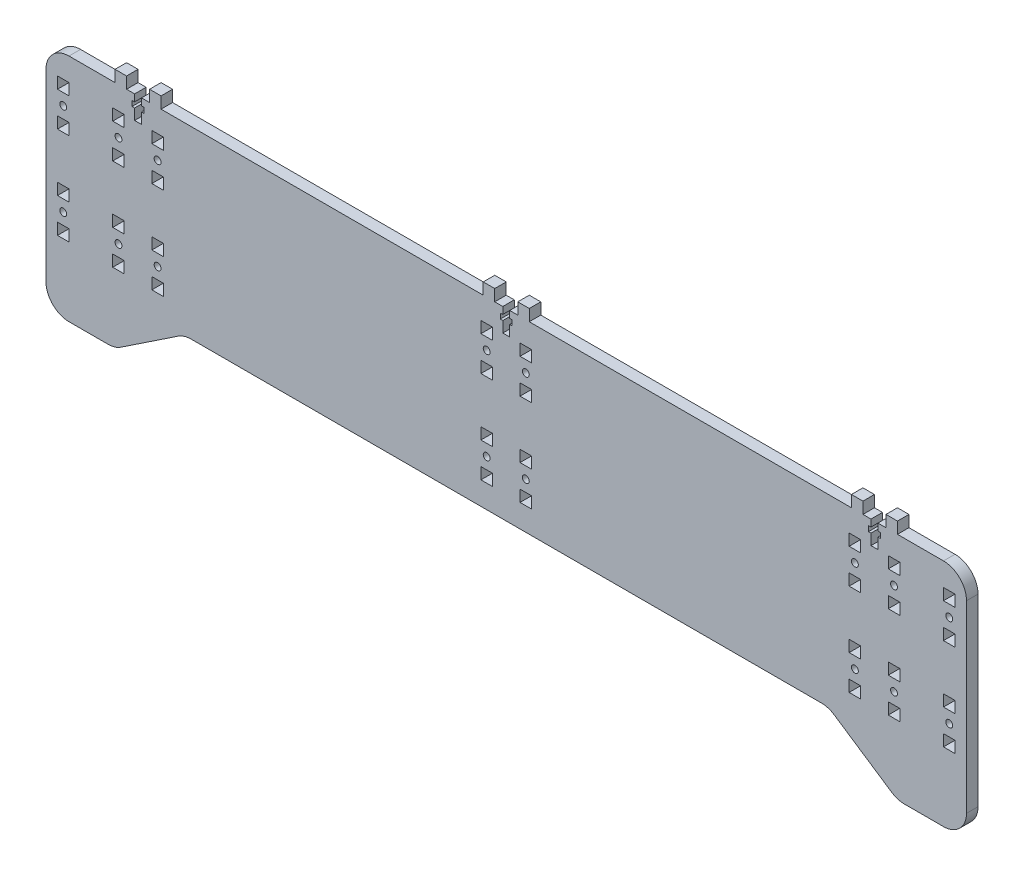
SolidWorks part; units mm, degrees
ref_plane "Front Plane" through (0, 0, 0) normal (0, 0, 1) x (1, 0, 0)
ref_plane "Top Plane" through (0, 0, 0) normal (0, 1, 0) x (1, 0, 0)
ref_plane "Right Plane" through (0, 0, 0) normal (1, 0, 0) x (0, 0, -1)
sketch "Sketch1" plane through (0, 0, 0) normal (0, 0, 1) x (1, 0, 0)
  line L0 (0, 0) -> (194.9917, 0) construction
  line L1 (0, 0) -> (0, -11.2208) construction
  line L2 (1.5, 0) -> (5, 0)
  line L3 (5, 5) -> (10, 5)
  line L4 (10, 5) -> (10, 0)
  line L5 (5, 5) -> (5, 0)
  line L6 (-1.5, 0) -> (-5, 0)
  line L7 (-5, 0) -> (-5, 5)
  line L8 (-5, 5) -> (-10, 5)
  line L9 (-10, 5) -> (-10, 0)
  line L10 (1.5, 0) -> (-1.5, 0) construction
  line L11 (-1.5, 0) -> (-1.5, -3)
  line L12 (-1.5, -5.3) -> (-2.6, -5.3)
  line L13 (2.6, -3) -> (2.6, -5.3)
  line L14 (-2.6, -3) -> (-1.5, -3)
  line L15 (-1.5, -5.3) -> (-1.5, -10)
  line L16 (-1.5, -10) -> (1.5, -10)
  line L17 (1.5, -10) -> (1.5, -5.3)
  line L18 (1.5, -3) -> (2.6, -3)
  line L19 (-2.6, -5.3) -> (-2.6, -3)
  line L20 (2.6, -5.3) -> (1.5, -5.3)
  line L21 (1.5, -3) -> (1.5, 0)
  line L22 (0, -10) -> (0, 0) construction
  line L23 (170, 5) -> (170, 0)
  line L24 (165, 5) -> (170, 5)
  line L25 (165, 5) -> (165, 0)
  line L26 (161.5, 0) -> (165, 0)
  line L27 (161.5, -3) -> (161.5, 0)
  line L28 (161.5, -3) -> (162.6, -3)
  line L29 (162.6, -3) -> (162.6, -5.3)
  line L30 (162.6, -5.3) -> (161.5, -5.3)
  line L31 (161.5, -10) -> (161.5, -5.3)
  line L32 (158.5, -10) -> (161.5, -10)
  line L33 (158.5, -5.3) -> (158.5, -10)
  line L34 (158.5, -5.3) -> (157.4, -5.3)
  line L35 (157.4, -5.3) -> (157.4, -3)
  line L36 (157.4, -3) -> (158.5, -3)
  line L37 (158.5, 0) -> (158.5, -3)
  line L38 (158.5, 0) -> (155, 0)
  line L39 (155, 0) -> (155, 5)
  line L40 (155, 5) -> (150, 5)
  line L41 (150, 5) -> (150, 0)
  line L42 (0, 0) -> (0, -60) construction
  line L43 (-150, 5) -> (-150, 0)
  line L44 (-155, 5) -> (-150, 5)
  line L45 (-155, 0) -> (-155, 5)
  line L46 (-158.5, 0) -> (-155, 0)
  line L47 (-158.5, 0) -> (-158.5, -3)
  line L48 (-157.4, -3) -> (-158.5, -3)
  line L49 (-157.4, -5.3) -> (-157.4, -3)
  line L50 (-158.5, -5.3) -> (-157.4, -5.3)
  line L51 (-158.5, -5.3) -> (-158.5, -10)
  line L52 (-158.5, -10) -> (-161.5, -10)
  line L53 (-161.5, -10) -> (-161.5, -5.3)
  line L54 (-162.6, -5.3) -> (-161.5, -5.3)
  line L55 (-162.6, -3) -> (-162.6, -5.3)
  line L56 (-161.5, -3) -> (-162.6, -3)
  line L57 (-161.5, -3) -> (-161.5, 0)
  line L58 (-161.5, 0) -> (-165, 0)
  line L59 (-165, 5) -> (-165, 0)
  line L60 (-165, 5) -> (-170, 5)
  line L61 (-170, 5) -> (-170, 0)
  line L63 (-10, 0) -> (-150, 0)
  line L64 (-170, 0) -> (-200, 0)
  line L65 (-200, 0) -> (-200, -100)
  line L66 (-200, -100) -> (200, -100) construction
  line L67 (200, -100) -> (200, 0)
  line L68 (200, 0) -> (170, 0)
  line L69 (10, 0) -> (150, 0)
  line L70 (-200, -60) -> (200, -60) construction
  line L71 (-160, -10) -> (-160, -60) construction
  line L72 (160, -10) -> (160, -60) construction
  line L73 (-151.5, -20) -> (-151.5, -60) construction
  line L74 (-200, -100) -> (-170, -100)
  line L75 (-170, -100) -> (-140, -80)
  line L76 (-140, -80) -> (140, -80)
  line L77 (140, -80) -> (170, -100)
  line L78 (170, -100) -> (200, -100)
  point P31 (0, -34.8981)
  point P84 (0, 0)
  point P85 (0, 0)
  line B0 (151.5, -55) -> (151.5, -65) construction
  line B1 (154, -55) -> (154, -50)
  line B2 (154, -55) -> (149, -55)
  line B3 (149, -55) -> (149, -50)
  line B4 (154, -50) -> (149, -50)
  line B5 (154, -65) -> (154, -70)
  line B6 (154, -65) -> (149, -65)
  line B7 (149, -65) -> (149, -70)
  line B8 (154, -70) -> (149, -70)
  line B9 (151.5, -60) -> (158.4724, -60) construction
  circle B10 centre (151.5, -60) radius 1.5
  line B11 (8.5, -55) -> (8.5, -65) construction
  line B12 (11, -55) -> (11, -50)
  line B13 (11, -55) -> (6, -55)
  line B14 (6, -55) -> (6, -50)
  line B15 (11, -50) -> (6, -50)
  line B16 (11, -65) -> (11, -70)
  line B17 (11, -65) -> (6, -65)
  line B18 (6, -65) -> (6, -70)
  line B19 (11, -70) -> (6, -70)
  line B20 (8.5, -60) -> (15.4724, -60) construction
  circle B21 centre (8.5, -60) radius 1.5
  line B22 (-151.5, -55) -> (-151.5, -65) construction
  line B23 (-149, -55) -> (-149, -50)
  line B24 (-149, -55) -> (-154, -55)
  line B25 (-154, -55) -> (-154, -50)
  line B26 (-149, -50) -> (-154, -50)
  line B27 (-149, -65) -> (-149, -70)
  line B28 (-149, -65) -> (-154, -65)
  line B29 (-154, -65) -> (-154, -70)
  line B30 (-149, -70) -> (-154, -70)
  line B31 (-151.5, -60) -> (-144.5276, -60) construction
  circle B32 centre (-151.5, -60) radius 1.5
  line B33 (-151.5, -15) -> (-151.5, -25) construction
  line B34 (-149, -15) -> (-149, -10)
  line B35 (-149, -15) -> (-154, -15)
  line B36 (-154, -15) -> (-154, -10)
  line B37 (-149, -10) -> (-154, -10)
  line B38 (-149, -25) -> (-149, -30)
  line B39 (-149, -25) -> (-154, -25)
  line B40 (-154, -25) -> (-154, -30)
  line B41 (-149, -30) -> (-154, -30)
  line B42 (-151.5, -20) -> (-144.5276, -20) construction
  circle B43 centre (-151.5, -20) radius 1.5
  line B44 (8.5, -15) -> (8.5, -25) construction
  line B45 (11, -15) -> (11, -10)
  line B46 (11, -15) -> (6, -15)
  line B47 (6, -15) -> (6, -10)
  line B48 (11, -10) -> (6, -10)
  line B49 (11, -25) -> (11, -30)
  line B50 (11, -25) -> (6, -25)
  line B51 (6, -25) -> (6, -30)
  line B52 (11, -30) -> (6, -30)
  line B53 (8.5, -20) -> (15.4724, -20) construction
  circle B54 centre (8.5, -20) radius 1.5
  line B55 (151.5, -15) -> (151.5, -25) construction
  line B56 (154, -15) -> (154, -10)
  line B57 (154, -15) -> (149, -15)
  line B58 (149, -15) -> (149, -10)
  line B59 (154, -10) -> (149, -10)
  line B60 (154, -25) -> (154, -30)
  line B61 (154, -25) -> (149, -25)
  line B62 (149, -25) -> (149, -30)
  line B63 (154, -30) -> (149, -30)
  line B64 (151.5, -20) -> (158.4724, -20) construction
  circle B65 centre (151.5, -20) radius 1.5
  line B66 (192.5, -15) -> (192.5, -25) construction
  line B67 (195, -15) -> (195, -10)
  line B68 (195, -15) -> (190, -15)
  line B69 (190, -15) -> (190, -10)
  line B70 (195, -10) -> (190, -10)
  line B71 (195, -25) -> (195, -30)
  line B72 (195, -25) -> (190, -25)
  line B73 (190, -25) -> (190, -30)
  line B74 (195, -30) -> (190, -30)
  line B75 (192.5, -20) -> (199.4724, -20) construction
  circle B76 centre (192.5, -20) radius 1.5
  line B77 (192.5, -55) -> (192.5, -65) construction
  line B78 (195, -55) -> (195, -50)
  line B79 (195, -55) -> (190, -55)
  line B80 (190, -55) -> (190, -50)
  line B81 (195, -50) -> (190, -50)
  line B82 (195, -65) -> (195, -70)
  line B83 (195, -65) -> (190, -65)
  line B84 (190, -65) -> (190, -70)
  line B85 (195, -70) -> (190, -70)
  line B86 (192.5, -60) -> (199.4724, -60) construction
  circle B87 centre (192.5, -60) radius 1.5
  line B88 (-192.5, -55) -> (-192.5, -65) construction
  line B89 (-190, -55) -> (-190, -50)
  line B90 (-190, -55) -> (-195, -55)
  line B91 (-195, -55) -> (-195, -50)
  line B92 (-190, -50) -> (-195, -50)
  line B93 (-190, -65) -> (-190, -70)
  line B94 (-190, -65) -> (-195, -65)
  line B95 (-195, -65) -> (-195, -70)
  line B96 (-190, -70) -> (-195, -70)
  line B97 (-192.5, -60) -> (-185.5276, -60) construction
  circle B98 centre (-192.5, -60) radius 1.5
  line B99 (-192.5, -15) -> (-192.5, -25) construction
  line B100 (-190, -15) -> (-190, -10)
  line B101 (-190, -15) -> (-195, -15)
  line B102 (-195, -15) -> (-195, -10)
  line B103 (-190, -10) -> (-195, -10)
  line B104 (-190, -25) -> (-190, -30)
  line B105 (-190, -25) -> (-195, -25)
  line B106 (-195, -25) -> (-195, -30)
  line B107 (-190, -30) -> (-195, -30)
  line B108 (-192.5, -20) -> (-185.5276, -20) construction
  circle B109 centre (-192.5, -20) radius 1.5
  line B110 (171, -15) -> (171, -10)
  line B111 (171, -15) -> (166, -15)
  line B112 (166, -15) -> (166, -10)
  line B113 (171, -10) -> (166, -10)
  line B114 (171, -25) -> (171, -30)
  line B115 (171, -25) -> (166, -25)
  line B116 (166, -25) -> (166, -30)
  line B117 (171, -30) -> (166, -30)
  line B118 (168.5, -20) -> (175.4724, -20) construction
  circle B119 centre (168.5, -20) radius 1.5
  line B120 (171, -55) -> (171, -50)
  line B121 (171, -55) -> (166, -55)
  line B122 (166, -55) -> (166, -50)
  line B123 (171, -50) -> (166, -50)
  line B124 (171, -65) -> (171, -70)
  line B125 (171, -65) -> (166, -65)
  line B126 (166, -65) -> (166, -70)
  line B127 (171, -70) -> (166, -70)
  line B128 (168.5, -60) -> (175.4724, -60) construction
  circle B129 centre (168.5, -60) radius 1.5
  line B130 (-11, -55) -> (-11, -50)
  line B131 (-11, -55) -> (-6, -55)
  line B132 (-6, -55) -> (-6, -50)
  line B133 (-11, -50) -> (-6, -50)
  line B134 (-11, -65) -> (-11, -70)
  line B135 (-11, -65) -> (-6, -65)
  line B136 (-6, -65) -> (-6, -70)
  line B137 (-11, -70) -> (-6, -70)
  circle B138 centre (-8.5, -60) radius 1.5
  line B139 (-11, -15) -> (-11, -10)
  line B140 (-11, -15) -> (-6, -15)
  line B141 (-6, -15) -> (-6, -10)
  line B142 (-11, -10) -> (-6, -10)
  line B143 (-11, -25) -> (-11, -30)
  line B144 (-11, -25) -> (-6, -25)
  line B145 (-6, -25) -> (-6, -30)
  line B146 (-11, -30) -> (-6, -30)
  circle B147 centre (-8.5, -20) radius 1.5
  line B148 (-171, -55) -> (-171, -50)
  line B149 (-171, -55) -> (-166, -55)
  line B150 (-166, -55) -> (-166, -50)
  line B151 (-171, -50) -> (-166, -50)
  line B152 (-171, -65) -> (-171, -70)
  line B153 (-171, -65) -> (-166, -65)
  line B154 (-166, -65) -> (-166, -70)
  line B155 (-171, -70) -> (-166, -70)
  circle B156 centre (-168.5, -60) radius 1.5
  line B157 (-171, -15) -> (-171, -10)
  line B158 (-171, -15) -> (-166, -15)
  line B159 (-166, -15) -> (-166, -10)
  line B160 (-171, -10) -> (-166, -10)
  line B161 (-171, -25) -> (-171, -30)
  line B162 (-171, -25) -> (-166, -25)
  line B163 (-166, -25) -> (-166, -30)
  line B164 (-171, -30) -> (-166, -30)
  circle B165 centre (-168.5, -20) radius 1.5
  dimension "D1" = 10
  dimension "D2" = 20
  dimension "D3" = 5
  dimension "D4" = 5.2
  dimension "D5" = 3
  dimension "D6" = 2.3
  dimension "D7" = 3
  dimension "D8" = 10
  dimension "D10" = 40
  dimension "D11" = 30
  dimension "D12" = 100
  dimension "D13" = 160
  dimension "D14" = 8.5
  dimension "D15" = 5
  dimension "D16" = 8.5
  dimension "D17" = 8.5
  dimension "D18" = 5
  dimension "D19" = 30
  dimension "D20" = 20
  dimension "D21" = 30
  dimension "D9" = 2
sketch_block_instance "Trou M3 plots 5mm-1"
sketch_block "Block1" parameters "D2"=3, "D1"=5, "D3"=5, "D4"=10
sketch_block_instance "Block1-1"
sketch_block_instance "Block1-2"
sketch_block_instance "Block1-3"
sketch_block_instance "Block1-4"
sketch_block_instance "Block1-5"
sketch_block_instance "Block1-7"
sketch_block_instance "Block1-8"
sketch_block_instance "Block1-9"
sketch_block_instance "Block1-10"
sketch_block_instance "Block1-16"
sketch_block_instance "Block1-17"
sketch_block_instance "Block1-27"
sketch_block_instance "Block1-28"
sketch_block_instance "Block1-29"
sketch_block_instance "Block1-30"
extrude "Boss-Extrude1" add sketch "Sketch1" along normal blind 5
fillet "Congé1" radius 10 8 edges at (200, 0, 2.5) (-200, 0, 2.5) (200, -100, 2.5) (170, -100, 2.5) (140, -80, 2.5) (-140, -80, 2.5) (-170, -100, 2.5) (-200, -100, 2.5)
